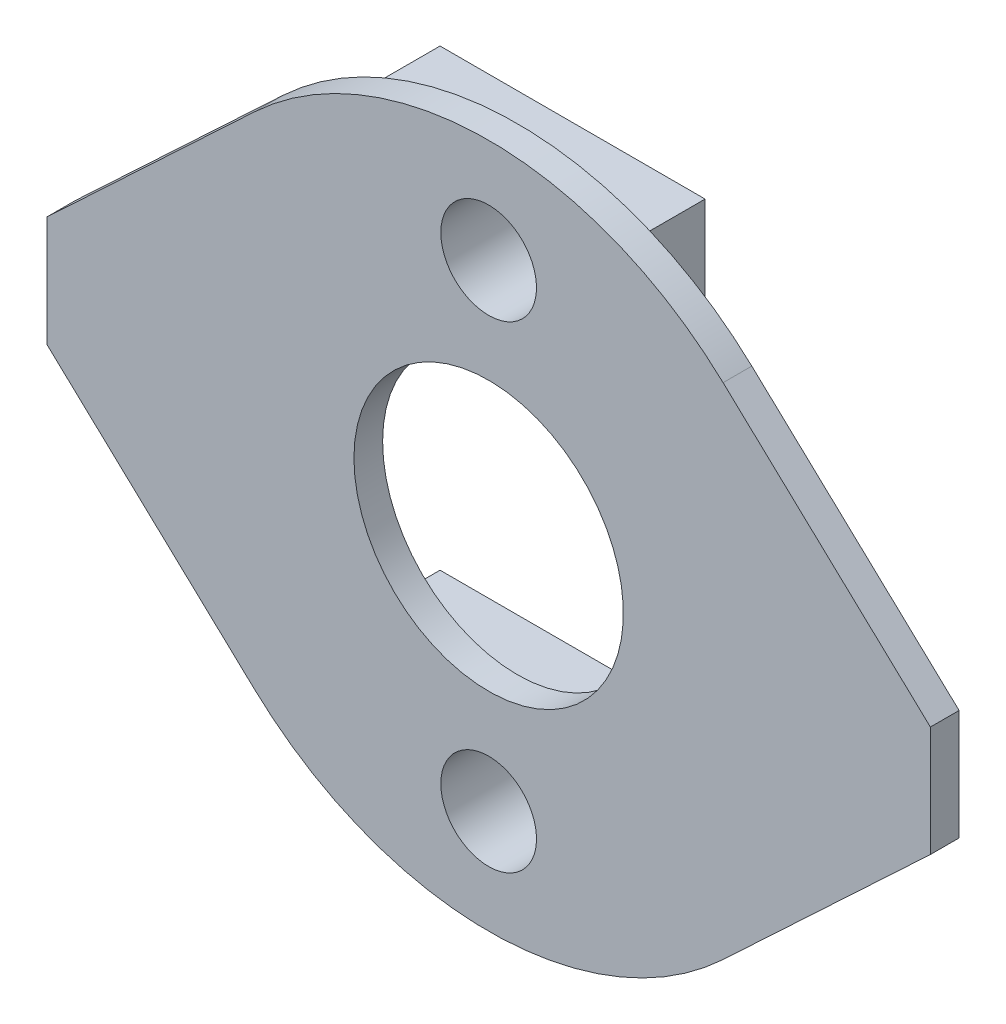
SolidWorks part; units mm, degrees
ref_plane "Front Plane" through (0, 0, 0) normal (0, 0, 1) x (1, 0, 0)
ref_plane "Top Plane" through (0, 0, 0) normal (0, 1, 0) x (1, 0, 0)
ref_plane "Right Plane" through (0, 0, 0) normal (1, 0, 0) x (0, 0, -1)
sketch "Sketch1" plane through (0, 0, 0) normal (0, 0, 1) x (1, 0, 0)
  line L0 (31.75, -139.7) -> (31.75, 139.7) construction
  line L1 (31.75, 12.7226) -> (37.7099, 12.7226)
  line L2 (31.75, 12.7226) -> (31.75, 6.3726)
  line L3 (31.75, 6.3726) -> (37.7099, 6.3726)
  line L5 (31.75, 12.7226) -> (37.7099, 6.3726) construction
  line L6 (31.75, 6.3726) -> (37.7099, 12.7226) construction
  line L7 (82.55, -139.7) -> (82.55, 139.7) construction
  line L8 (76.5901, 12.7226) -> (82.55, 12.7226)
  line L10 (76.5901, 6.3726) -> (82.55, 6.3726)
  line L11 (82.55, 12.7226) -> (82.55, 6.3726)
  line L12 (76.5901, 12.7226) -> (82.55, 6.3726) construction
  line L13 (76.5901, 6.3726) -> (82.55, 12.7226) construction
  line L14 (57.15, -10.15) -> (57.15, 1.8006)
  line L15 (31.75, 6.3726) -> (43.6698, -4.8149)
  line L16 (31.75, 12.7226) -> (43.6698, 23.9102)
  line L17 (82.55, 6.3726) -> (70.6302, -4.8149)
  line L18 (82.55, 12.7226) -> (70.6302, 23.9102)
  line L19 (57.15, 17.2946) -> (57.15, 29.2453) construction
  arc A2 (37.7099, 6.3726) -> (76.5901, 6.3726) centre (57.15, 9.5476) ccw
  circle A3 centre (57.15, 9.5476) radius 7.747
  arc A4 (76.5901, 12.7226) -> (37.7099, 12.7226) centre (57.15, 9.5476) ccw
  circle A5 centre (57.15, -4.1747) radius 2.75
  circle A6 centre (57.15, 23.27) radius 2.75
  circle A7 centre (72.6, -136.95) radius 2.75 construction
  point P8 (34.73, 9.5476)
  point P15 (79.57, 9.5476)
  point P26 (57.15, 23.27)
  point P33 (57.15, -4.1747)
  dimension "D1" = 15.494
  dimension "D2" = 6.35
extrude "Boss-Extrude1" add sketch "Sketch1" along normal up to surface (1.65 mm away)
sketch "Sketch2" plane through (0, 0, 0) normal (0, 0, -1) x (-1, 0, 0)
  line L0 (-49.53, 139.7) -> (-49.53, -139.7) construction
  line L1 (-64.77, 27.7117) -> (-49.53, 27.7117)
  line L2 (-64.77, 27.7117) -> (-64.77, 17.4851)
  line L3 (-64.77, 17.4851) -> (-49.53, 17.4851)
  line L4 (-49.53, 27.7117) -> (-49.53, 17.4851)
  line L7 (-64.77, 139.7) -> (-64.77, -139.7) construction
  line L8 (-64.77, -8.6164) -> (-49.53, -8.6164)
  line L9 (-64.77, -8.6164) -> (-64.77, 1.6101)
  line L10 (-64.77, 1.6101) -> (-49.53, 1.6101)
  line L11 (-49.53, -8.6164) -> (-49.53, 1.6101)
  arc A0 (-43.6698, 23.9102) -> (-70.6302, 23.9102) centre (-57.15, 9.5476) ccw construction
  arc A1 (-70.6302, -4.8149) -> (-43.6698, -4.8149) centre (-57.15, 9.5476) ccw construction
  circle A2 centre (-57.15, 9.5476) radius 7.9375 construction
  circle A3 centre (-57.15, -4.1747) radius 2.75
  circle A4 centre (-57.15, 23.27) radius 2.75
  circle A6 centre (-57.15, -4.1747) radius 2.75 construction
  circle M10 centre (-57.15, -4.1747) radius 2.75
  circle M11 centre (-57.15, 23.27) radius 2.75
extrude "Boss-Extrude3" add sketch "Sketch2" along normal blind 3.175 contours L4 L1 L2 L3 M11 | L8 L11 L10 L9 M10
